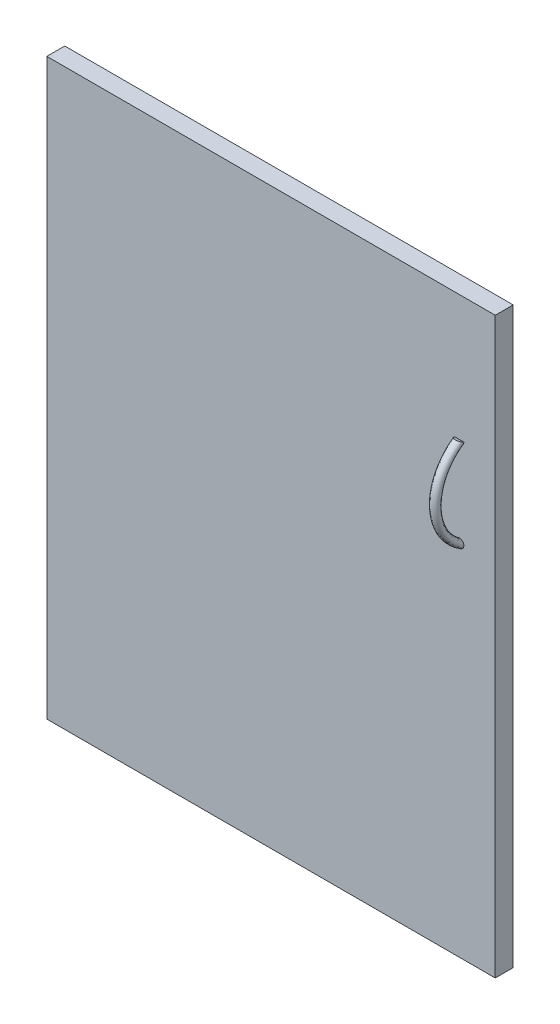
SolidWorks part; units mm, degrees
ref_plane "前基準面" through (0, 0, 0) normal (0, 0, 1) x (1, 0, 0)
ref_plane "上基準面" through (0, 0, 0) normal (0, 1, 0) x (1, 0, 0)
ref_plane "右基準面" through (0, 0, 0) normal (1, 0, 0) x (0, 0, -1)
sketch "草圖1" plane through (0, 0, 0) normal (0, 0, 1) x (1, 0, 0)
  line L1 (-12.5, 16) -> (12.5, 16)
  line L2 (-12.5, 16) -> (-12.5, -16)
  line L3 (-12.5, -16) -> (12.5, -16)
  line L4 (12.5, 16) -> (12.5, -16)
  line L5 (-12.5, 16) -> (12.5, -16) construction
  line L6 (-12.5, -16) -> (12.5, 16) construction
  point P0 (0, 0)
  dimension "D1" = 25
  dimension "D2" = 32
extrude "填料-伸長1" add sketch "草圖1" along normal blind 1
ref_plane "平面1" through (10.5, 0, 0) normal (1, 0, 0) x (0, 0, -1)
sketch "草圖3" plane through (0, 0, 1) normal (0, 0, 1) x (1, 0, 0)
  line L0 (10.5, 16) -> (10.5, -16) construction
  line L1 (12.5, 16) -> (-12.5, 16) construction
  line L2 (-12.5, -16) -> (12.5, -16) construction
  line L3 (12.5, -16) -> (12.5, 16) construction
  circle A0 centre (10.5, 4) radius 0.25
  dimension "D2" = 0.5
  dimension "D1" = 2
  dimension "D3" = 20
sketch "草圖4" plane through (10.5, 0, 0) normal (1, 0, 0) x (0, 0, -1)
  line L0 (-1, 16) -> (-1, -16) construction
  arc A0 (-1, 4) -> (-1, 9) centre (0.6583, 6.5) cw
  point P4 (1.1734, -1.432)
  dimension "D1" = 3
  dimension "D2" = 5
sweep "掃出1" add profiles "草圖3" path "草圖4"
